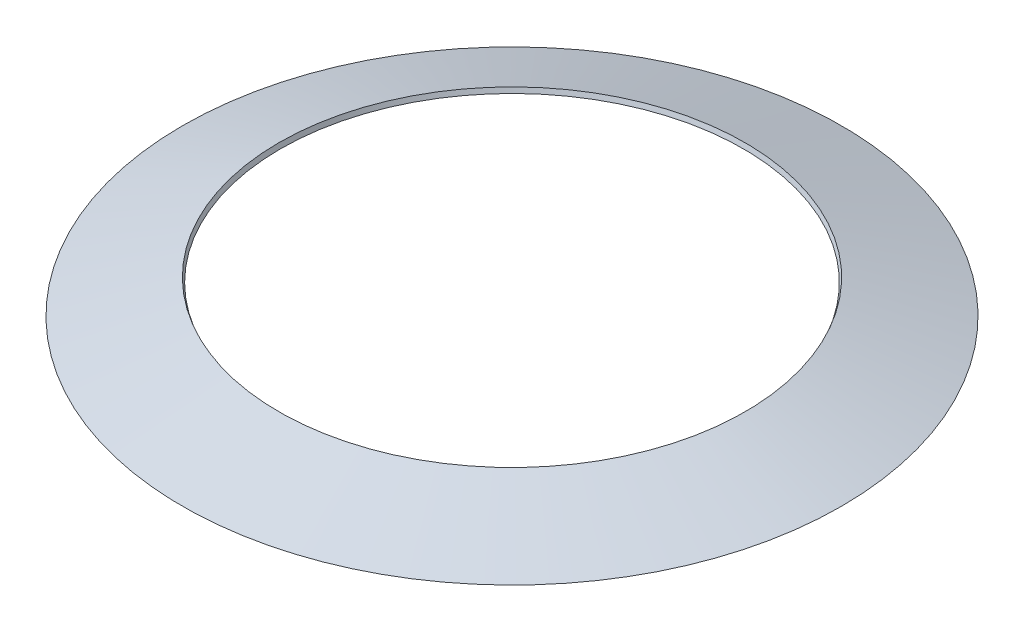
SolidWorks part; units mm, degrees
ref_plane "Plan1" through (0, 0, 0) normal (0, 0, 1) x (1, 0, 0)
ref_plane "Plan2" through (0, 0, 0) normal (0, 1, 0) x (1, 0, 0)
ref_plane "Plan3" through (0, 0, 0) normal (1, 0, 0) x (0, 0, -1)
sketch "Esquisse1" plane through (0, 0, 0) normal (0, 0, 1) x (1, 0, 0)
  line L0 (68, 17.8199) -> (48.0964, 24.7511)
  line L1 (0, 41.5) -> (68, 17.8199) construction
  line L2 (0, -60) -> (0, -90) construction
  line L3 (0, 45.4963) -> (0, -204.5037) construction
revolve "Base-Révol.-Mince" add sketch "Esquisse1" angle 360 about L2
sketch "Esquisse2" plane through (0, 0, 0) normal (0, 0, 1) x (1, 0, 0)
  line L0 (-68, 17.8199) -> (68, 17.8199)
  line L4 (68, 17.8199) -> (68, 16.8755)
  line L5 (68, 16.8755) -> (-68, 16.8755)
  line L6 (-68, 16.8755) -> (-68, 17.8199)
  line L8 (67.6711, 16.8755) -> (68, 17.8199) construction
  line L9 (-68, 17.8199) -> (-67.6711, 16.8755) construction
  line L10 (-68, 17.8199) -> (68, 17.8199) construction
  line L11 (-67.6711, 16.8755) -> (67.6711, 16.8755) construction
extrude "Enlèv. mat.-Extru.1" cut sketch "Esquisse2" against normal through all and the other way through all
sketch "sommet roue" plane through (0, 0, 0) normal (1, 0, 0) x (0, 0, -1)
  line L0 (68, 17.8199) -> (48.0964, 24.7511) construction
  line L1 (-48.0964, 24.7511) -> (-68, 17.8199) construction
  point P0 (0, 41.5)
